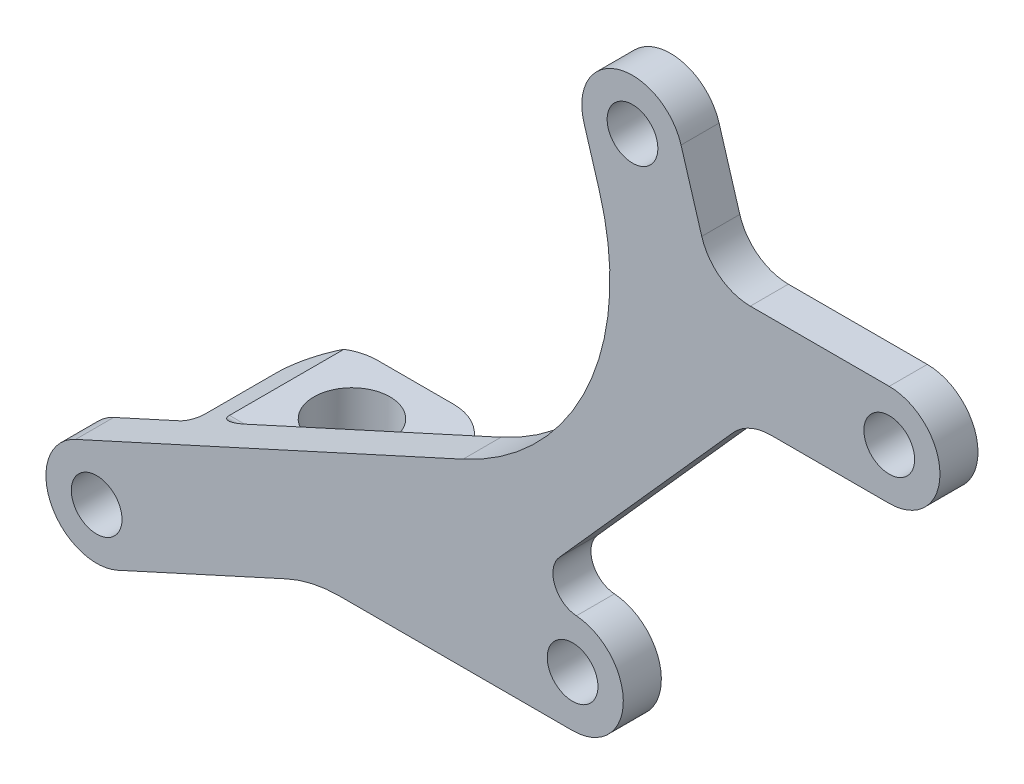
SolidWorks part; units mm, degrees
ref_plane "Plan de face" through (0, 0, 0) normal (0, 0, 1) x (1, 0, 0)
ref_plane "Plan de dessus" through (0, 0, 0) normal (0, 1, 0) x (1, 0, 0)
ref_plane "Plan de droite" through (0, 0, 0) normal (1, 0, 0) x (0, 0, -1)
sketch "Esquisse1" plane through (0, 0, 0) normal (0, 0, 1) x (1, 0, 0)
  line L0 (5.7259, 0) -> (16, 0)
  line L2 (16, 4.0012) -> (14, 4.0012)
  line L3 (14, 4.0012) -> (22.9191, 14.0012)
  line L4 (22.9191, 14.0012) -> (28.4872, 14.0012)
  line L6 (28.4872, 18.0012) -> (21.5221, 18.0012)
  line L11 (16, 2.0006) -> (28.4872, 16.0012) construction
  line L12 (-3.5973, 0.147) -> (11.6789, 7.1087)
  line L15 (17.0539, 18.9689) -> (16.4475, 20.9852)
  line L17 (-5.2384, -0.381) -> (1.3589, 2.6254) construction
  line L18 (-1.9386, -3.4928) -> (5.7259, 0)
  line L20 (20.2779, 22.1373) -> (21.5221, 18.0012)
  arc A0 (28.4872, 14.0012) -> (28.4872, 18.0012) centre (28.4872, 16.0012) ccw
  arc A2 (16, 0) -> (16, 4.0012) centre (16, 2.0006) ccw
  circle A5 centre (28.4872, 16.0012) radius 1
  circle A6 centre (16, 2.0006) radius 1
  arc A9 (20.2779, 22.1373) -> (16.4475, 20.9852) centre (18.3627, 21.5613) ccw
  circle A10 centre (18.3627, 21.5613) radius 1
  arc A14 (11.6789, 7.1087) -> (17.0539, 18.9689) centre (7.5735, 16.1173) ccw
  arc A15 (-3.5973, 0.147) -> (-1.9386, -3.4928) centre (-2.768, -1.6729) ccw
  circle A16 centre (-2.768, -1.6729) radius 1
  dimension "D14" = 10
  dimension "D15" = 2
  dimension "D16" = 2
  dimension "D2" = 4
  dimension "D4" = 3.5601
  dimension "D11" = 2
  dimension "D12" = 3.1593
  dimension "D5" = 2
  dimension "D3" = 4
  dimension "D8" = 48.27
  dimension "D18" = 6.9652
  dimension "D19" = 4
extrude "Boss.-Extru.1" add sketch "Esquisse1" along normal blind 1.5
fillet "Congé1" radius 2 2 edges at (22.9191, 14.0012, 0.75) (21.5221, 18.0012, 0.75)
fillet "Congé2" radius 1 1 edges at (14, 4.0012, 0.75)
sketch "Esquisse2" plane through (0, 0, 0) normal (0, 0, -1) x (-1, 0, 0)
  line L1 (-5.7259, 0) -> (-16, 0) construction
  line L9 (-6.5, 0) -> (0.5, 0)
  line L14 (-6.5, 0) -> (-6.5, 2)
  line L15 (-6.5, 2) -> (0.5, 2)
  line L16 (0.5, 0) -> (0.5, 2)
  arc A0 (-16.1496, 3.9956) -> (-16, 0) centre (-16, 2.0006) ccw construction
  dimension "D1" = 2
  dimension "D2" = 7
  dimension "D3" = 9.5
extrude "Boss.-Extru.2" add sketch "Esquisse2" along normal blind 5.3
fillet "Congé3" radius 0.5 1 edges at (3.4844, 2, 0)
fillet "Congé4" radius 0.5 1 edges at (-0.5, 0.7793, 0)
fillet "Congé5" radius 2 1 edges at (6.5, 1.25, 0)
fillet "Congé6" radius 2 2 edges at (-0.5, 1, -5.3) (6.5, 1, -5.3)
sketch "Esquisse3" plane through (0, 2, 0) normal (0, 1, 0) x (1, 0, 0)
  line L0 (6.5, 3.3) -> (6.5, 2) construction
  line L1 (1.5, 5.3) -> (4.5, 5.3) construction
  circle A0 centre (3, 2.8) radius 1.5
  dimension "D1" = 3
  dimension "D2" = 3.5
  dimension "D3" = 2.5
extrude "Enlèv. mat.-Extru.1" cut sketch "Esquisse3" against normal blind 5
fillet "Congé7" radius 5 1 edges at (5.7259, 0, 0.75)
sketch "Esquisse4" plane through (0, 0, 0) normal (0, 0, 1) x (1, 0, 0)
  line L0 (-0.5, 1.5585) -> (0.4687, 2)
  line L1 (0.4687, 2) -> (-0.5, 2)
  line L2 (-0.5, 2) -> (-0.5, 1.5585)
extrude "Enlèv. mat.-Extru.2" cut sketch "Esquisse4" against normal blind 6
